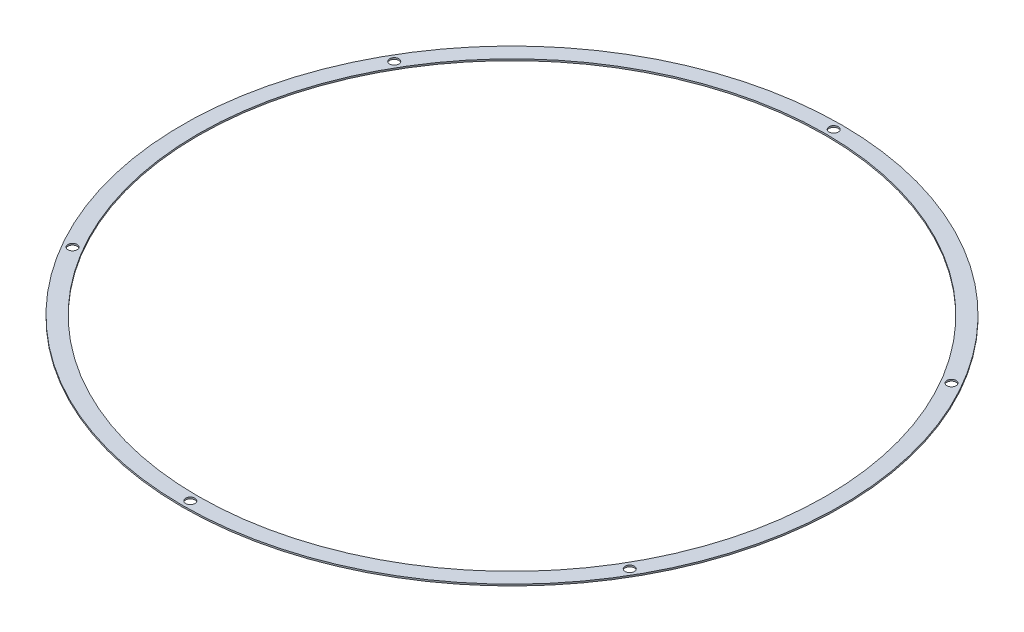
SolidWorks part; units mm, degrees
material "AISI 304"
ref_plane "Front Plane" through (0, 0, 0) normal (0, 0, 1) x (1, 0, 0)
ref_plane "Top Plane" through (0, 0, 0) normal (0, 1, 0) x (1, 0, 0)
ref_plane "Right Plane" through (0, 0, 0) normal (1, 0, 0) x (0, 0, -1)
sketch "Sketch1" plane through (0, 0, 0) normal (0, 1, 0) x (1, 0, 0)
  circle A0 centre (0, 0) radius 105
  circle A1 centre (0, 0) radius 100
  circle A2 centre (0, 0) radius 102.5 construction
  circle A3 centre (0, -102.5) radius 1.4732
  circle A4 centre (-88.7671, -51.2491) radius 1.4732
  circle A5 centre (-88.7661, 51.2509) radius 1.4732
  circle A6 centre (0.002, 102.5) radius 1.4732
  circle A7 centre (88.7691, 51.2491) radius 1.4732
  circle A8 centre (88.7681, -51.2509) radius 1.4732
  dimension "D1" = 210
  dimension "D3" = 205
  dimension "D4" = 2.9464
  dimension "D2" = 5
  dimension "D5" = 6
extrude "Boss-Extrude1" add sketch "Sketch1" along normal blind 0.508 contours A0 A8 A7 A6 A5 A4 A3 A1
